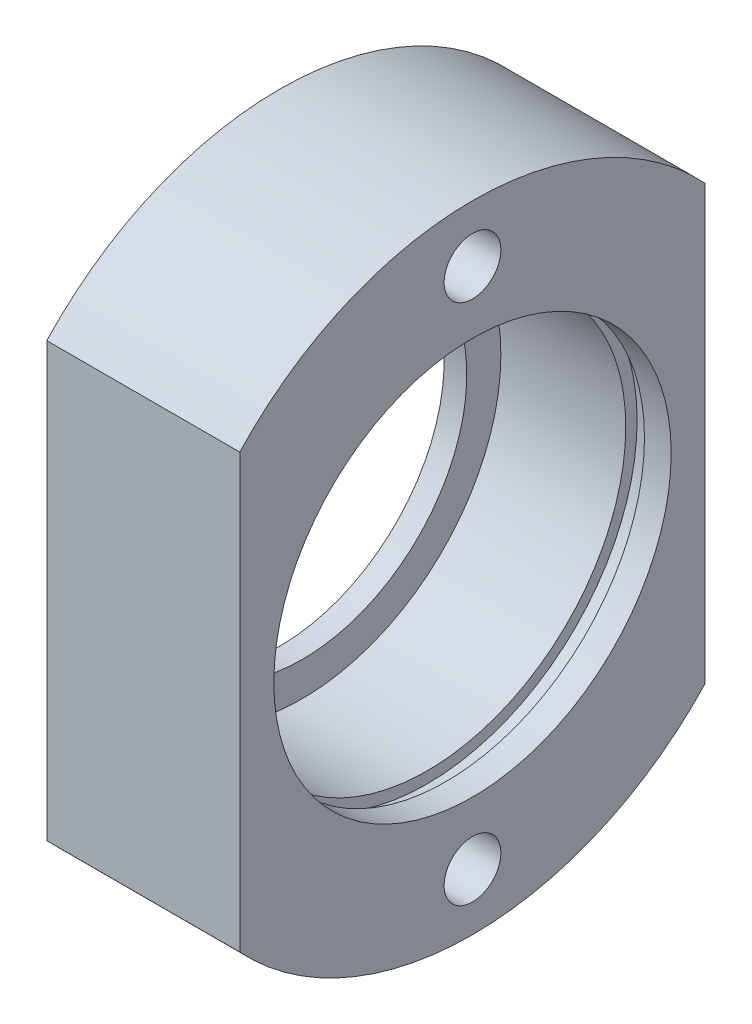
SolidWorks part; units mm, degrees
ref_plane "Front Plane" through (0, 0, 0) normal (0, 0, 1) x (1, 0, 0)
ref_plane "Top Plane" through (0, 0, 0) normal (0, 1, 0) x (1, 0, 0)
ref_plane "Right Plane" through (0, 0, 0) normal (1, 0, 0) x (0, 0, -1)
sketch "Sketch1" plane through (0, 0, 0) normal (0, 0, 1) x (1, 0, 0)
  line L0 (0, 0) -> (17, 0) construction
  line L1 (0, 28) -> (17, 28)
  line L2 (17, 28) -> (17, 17.5)
  line L3 (17, 17.5) -> (14.65, 17.5)
  line L4 (14.65, 17.5) -> (14.65, 18.5)
  line L5 (14.65, 18.5) -> (13, 18.5)
  line L6 (13, 18.5) -> (13, 17.5)
  line L7 (13, 17.5) -> (2, 17.5)
  line L8 (2, 17.5) -> (2, 14.5)
  line L9 (2, 14.5) -> (0, 14.5)
  line L10 (0, 14.5) -> (0, 28)
  line L11 (0, 7.5) -> (17, 7.5) construction
  dimension "D1" = 2
  dimension "DH_s" = 29
  dimension "D" = 35
  dimension "MSM_1" = 37
  dimension "MSM_2" = 1.65
  dimension "H" = 56
  dimension "B" = 11
  dimension "T" = 17
  dimension "D_s" = 15
revolve "Revolve1" add sketch "Sketch1" angle 360 about L0
sketch "Sketch2" plane through (17, 0, 0) normal (1, 0, 0) x (0, 0, -1)
  line L0 (-20.5, 19.0722) -> (-20.5, -19.0722)
  line L1 (20.5, 19.0722) -> (20.5, -19.0722)
  line L2 (0, 0) -> (0, 28) construction
  circle A0 centre (0, 0) radius 28 construction
  arc A1 (-20.5, 19.0722) -> (-20.5, -19.0722) centre (0, 0) ccw
  arc A2 (20.5, -19.0722) -> (20.5, 19.0722) centre (0, 0) ccw
  dimension "W" = 41
extrude "Cut-Extrude1" cut sketch "Sketch2" against normal through all
hole_wizard "Tapped Hole1" positions "Sketch4" profile "Sketch3" tap size "M6x1.0" standard "JIS" end condition through all
sketch "Sketch4" plane through (17, 0, 0) normal (1, 0, 0) x (0, 0, -1)
  line L0 (0, 23) -> (0, -23) construction
  point P0 (0, 23)
  point P2 (0, -23)
  dimension "A" = 46
sketch "Sketch3" plane through (17, 23, 0) normal (0, 1, 0) x (0, 0, -1)
  line L0 (0, 0) -> (0, 17)
  line L1 (0, 17) -> (2.5, 17)
  line L2 (2.5, 17) -> (2.5, 0)
  line L5 (2.5, 0) -> (0, 0)
  line L11 (0, 0) -> (0, 17) construction
  dimension "Thru Tap Drill Dia." = 5
  dimension "Thru Tap Drill Depth" = 17
cosmetic thread "Hole Thread1" parameters "M"=6
cosmetic thread "Hole Thread2" parameters "M"=6
hole_wizard "Tapped Hole2" [suppressed] positions "Sketch6" profile "Sketch5" tap size "M8x1.25" standard "JIS"
sketch "Sketch6" plane through (9, 0, 0) normal (1, 0, 0) x (0, 0, -1)
  line L0 (0, 0) -> (0, 32) construction
  line L3 (0, 0) -> (22, 0) construction
  line L4 (22, 23.2379) -> (22, -23.2379) construction
  arc A0 (22, 23.2379) -> (-22, 23.2379) centre (0, 0) ccw construction
  point P0 (12, 22.5)
  point P2 (-12, 22.5)
  point P4 (12, -22.5)
  point P6 (-12, -22.5)
  dimension "F" = 24
  dimension "A" = 46
sketch "Sketch5" plane through (9, 22.5, -12) normal (0, 1, 0) x (0, 0, -1)
  line L0 (0, 0) -> (0, 9)
  line L1 (0, 9) -> (3.4, 9)
  line L2 (3.4, 9) -> (3.4, 0)
  line L5 (3.4, 0) -> (0, 0)
  line L11 (0, 0) -> (0, 9) construction
  dimension "Thru Tap Drill Dia." = 6.8
  dimension "Thru Tap Drill Depth" = 9
cosmetic thread "Hole Thread3" [suppressed] parameters "M"=8
cosmetic thread "Hole Thread4" [suppressed] parameters "M"=8
cosmetic thread "Hole Thread5" [suppressed] parameters "M"=8
cosmetic thread "Hole Thread6" [suppressed] parameters "M"=8
equation "\"Tapped Hole1\" = if ( \"D_s@Sketch1\" < = 17 , \"unsuppressed\" , \"suppressed\" )"
equation "\"Hole Thread1\"= if ( \"D_s@Sketch1\" < = 17 , \"unsuppressed\" , \"suppressed\" )"
equation "\"Hole Thread2\"= if ( \"D_s@Sketch1\" < = 17 , \"unsuppressed\" , \"suppressed\" )"
equation "\"Tapped Hole2\" = if ( \"D_s@Sketch1\" > = 20 , \"unsuppressed\" , \"suppressed\" )"
equation "\"Hole Thread3\"= if ( \"D_s@Sketch1\" > = 20 , \"unsuppressed\" , \"suppressed\" )"
equation "\"Hole Thread4\"= if ( \"D_s@Sketch1\" > = 20 , \"unsuppressed\" , \"suppressed\" )"
equation "\"Hole Thread5\"= if ( \"D_s@Sketch1\" > = 20 , \"unsuppressed\" , \"suppressed\" )"
equation "\"Hole Thread6\"= if ( \"D_s@Sketch1\" > = 20 , \"unsuppressed\" , \"suppressed\" )"
